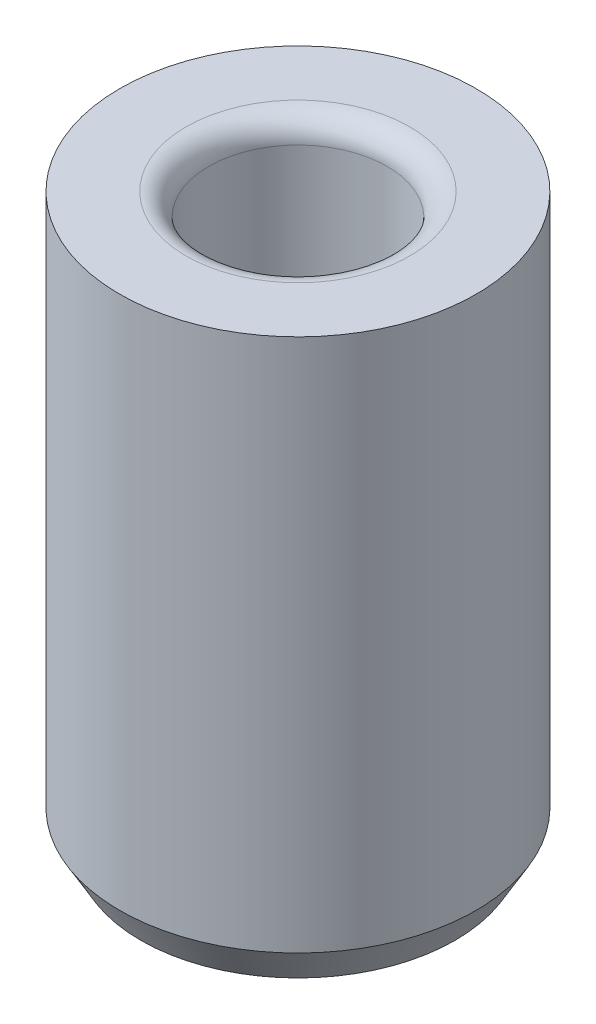
SolidWorks part; units mm, degrees
material "TOOL STEEL"
ref_plane "Front Plane" through (0, 0, 0) normal (0, 0, 1) x (1, 0, 0)
ref_plane "Top Plane" through (0, 0, 0) normal (0, 1, 0) x (1, 0, 0)
ref_plane "Right Plane" through (0, 0, 0) normal (1, 0, 0) x (0, 0, -1)
sketch "Sketch1" plane through (0, 0, 0) normal (0, 0, 1) x (1, 0, 0)
  line L0 (0, 0) -> (0, -12.7) construction
  line L1 (2.4924, 0) -> (3.9688, 0)
  line L2 (1.9844, -0.508) -> (1.9844, -12.319)
  line L3 (2.3654, -12.7) -> (3.9688, -12.7)
  line L4 (3.9688, 0) -> (3.9688, -12.7)
  line L5 (1.9844, -12.319) -> (2.3654, -12.7)
  arc A0 (2.4924, 0) -> (1.9844, -0.508) centre (2.4924, -0.508) ccw
  point P2 (1.9844, -12.7)
  dimension "D1" = 0.508
  dimension "L" = 12.7
  dimension "ID" = 3.9688
  dimension "OD" = 7.9375
revolve "BODY" add sketch "Sketch1" angle 360 about L0
chamfer "Chamfer1" distance 0.8128 angle 30 1 edges at (-3.9687, -12.7, 0)
sketch "Sketch2" plane through (0, 0, 0) normal (0, 1, 0) x (1, 0, 0)
  line L0 (0, -1.9844) -> (0, -1.2224) construction
  line L1 (-3.7758, -1.2224) -> (3.7758, -1.2224)
  line L2 (-3.7758, -1.2224) -> (-3.7758, -3.9688)
  line L3 (-3.7758, -3.9688) -> (3.7758, -3.9688)
  line L4 (3.7758, -1.2224) -> (3.7758, -3.9688)
  circle A0 centre (0, 0) radius 3.9688 construction
  circle A1 centre (0, 0) radius 1.9844 construction
  dimension "D2" = 0.762
extrude "Flat Cut" [suppressed] cut sketch "Sketch2" against normal blind 3.175
ref_plane "Plane1" through (0, 0, 0) normal (0, 1, 0) x (1, 0, 0)
